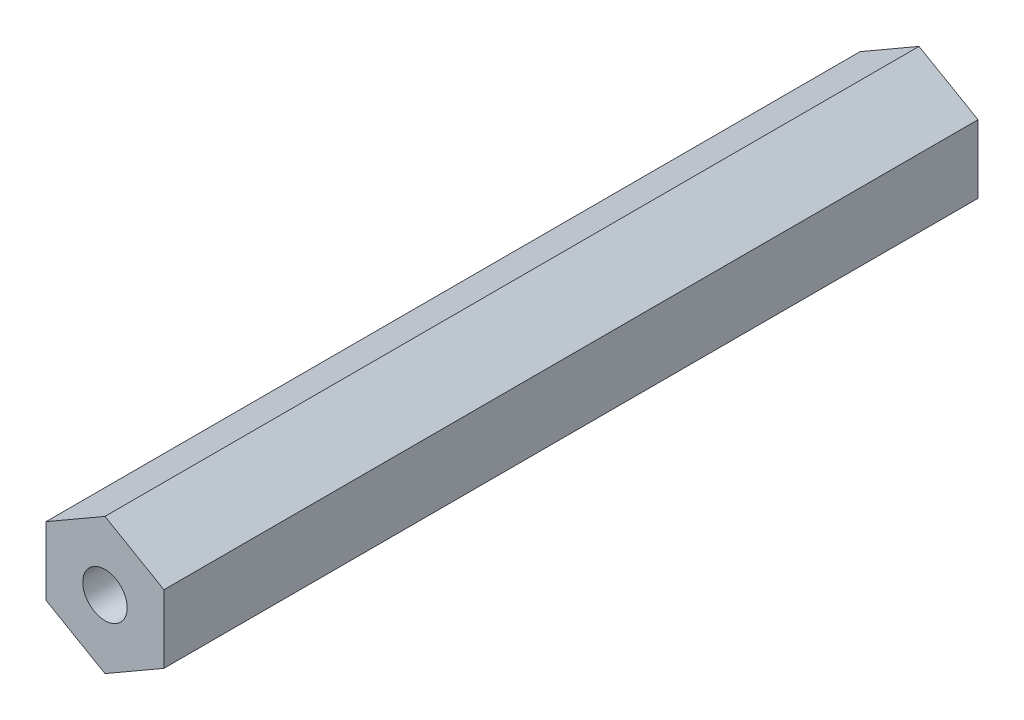
SolidWorks part; units mm, degrees
ref_plane "前视基准面" through (0, 0, 0) normal (0, 0, 1) x (1, 0, 0)
ref_plane "上视基准面" through (0, 0, 0) normal (0, 1, 0) x (1, 0, 0)
ref_plane "右视基准面" through (0, 0, 0) normal (1, 0, 0) x (0, 0, -1)
other "Configuration Table"
sketch "草图1" plane through (0, 0, 0) normal (0, 0, 1) x (1, 0, 0)
  line L0 (0, 0) -> (0, -9.0003) construction
  line L1 (3.9837, -2.3) -> (3.9837, 2.3)
  line L2 (3.9837, 2.3) -> (0, 4.6)
  line L3 (0, 4.6) -> (-3.9837, 2.3)
  line L4 (-3.9837, 2.3) -> (-3.9837, -2.3)
  line L5 (-3.9837, -2.3) -> (0, -4.6)
  line L6 (0, -4.6) -> (3.9837, -2.3)
  circle A0 centre (0, 0) radius 3.9837 construction
  circle A1 centre (0, 0) radius 1.5
  dimension "D2" = 3
  dimension "D1" = 4.6
extrude "凸台-拉伸1" add sketch "草图1" along normal blind 55
